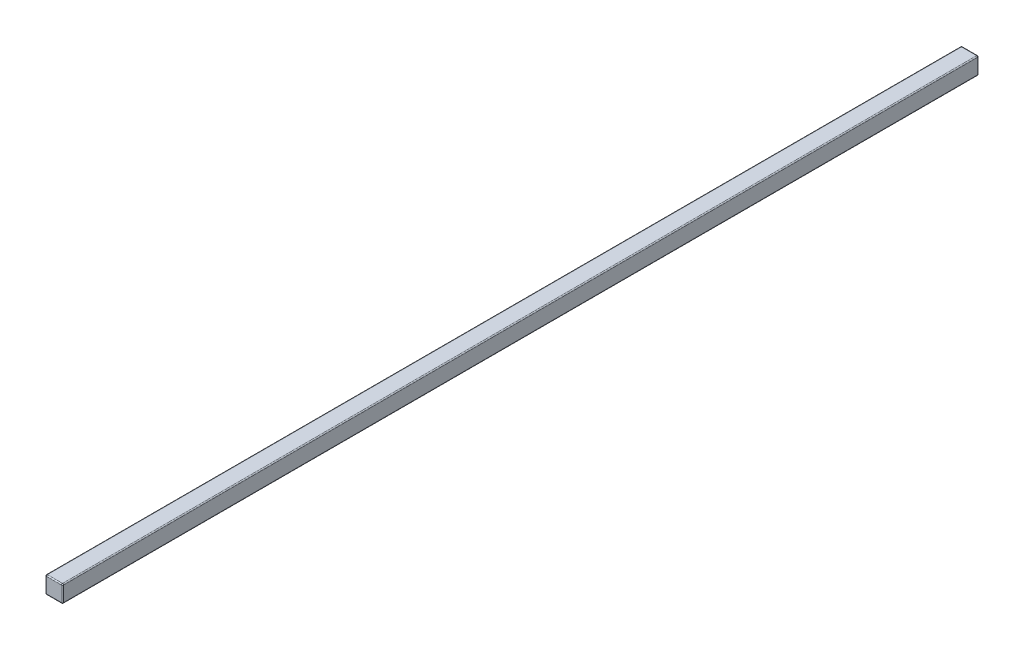
SolidWorks part; units mm, degrees
ref_plane "Front Plane" through (0, 0, 0) normal (0, 0, 1) x (1, 0, 0)
ref_plane "Top Plane" through (0, 0, 0) normal (0, 1, 0) x (1, 0, 0)
ref_plane "Right Plane" through (0, 0, 0) normal (1, 0, 0) x (0, 0, -1)
sketch "Sketch1" plane through (0, 0, 0) normal (0, 0, 1) x (1, 0, 0)
  line L1 (-12.5, -12.5) -> (12.5, -12.5)
  line L2 (-12.5, -12.5) -> (-12.5, 12.5)
  line L3 (-12.5, 12.5) -> (12.5, 12.5)
  line L4 (12.5, -12.5) -> (12.5, 12.5)
  line L5 (-12.5, -12.5) -> (12.5, 12.5) construction
  line L6 (-12.5, 12.5) -> (12.5, -12.5) construction
  point P0 (0, 0)
  dimension "D1" = 25
  dimension "D2" = 25
extrude "Boss-Extrude1" add sketch "Sketch1" along normal blind 1336.6
fillet "Fillet1" radius 1.5 12 edges at (0, -12.5, 1336.6) (0, -12.5, 0) (-12.5, 0, 1336.6) (-12.5, -12.5, 668.3) (-12.5, 0, 0) (12.5, -12.5, 668.3) (12.5, 0, 1336.6) (12.5, 0, 0) (12.5, 12.5, 668.3) (0, 12.5, 1336.6) (-12.5, 12.5, 668.3) (0, 12.5, 0)
